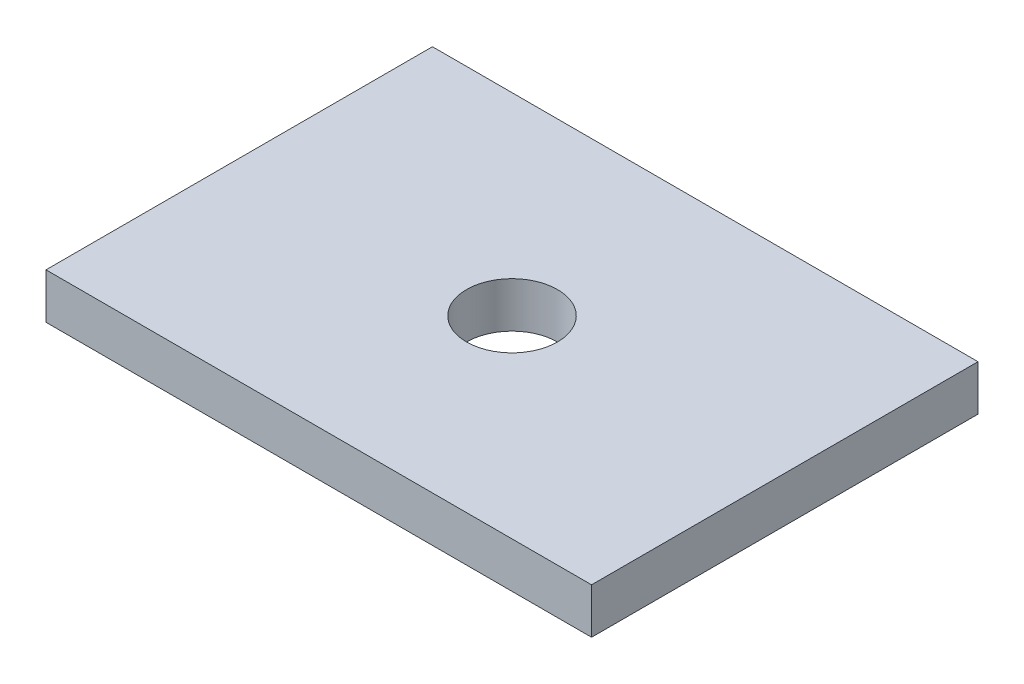
SolidWorks part; units mm, degrees
ref_plane "Front Plane" through (0, 0, 0) normal (0, 0, 1) x (1, 0, 0)
ref_plane "Top Plane" through (0, 0, 0) normal (0, 1, 0) x (1, 0, 0)
ref_plane "Right Plane" through (0, 0, 0) normal (1, 0, 0) x (0, 0, -1)
sketch "Sketch1" plane through (0, 0, 0) normal (0, 1, 0) x (1, 0, 0)
  line L1 (-24, 17) -> (24, 17)
  line L2 (-24, 17) -> (-24, -17)
  line L3 (-24, -17) -> (24, -17)
  line L4 (24, 17) -> (24, -17)
  line L5 (-24, 17) -> (24, -17) construction
  line L6 (-24, -17) -> (24, 17) construction
  circle A0 centre (0, 0) radius 4
  point P0 (0, 0)
  dimension "D3" = 8
  dimension "D1" = 48
  dimension "D2" = 34
extrude "Boss-Extrude1" add sketch "Sketch1" along normal blind 4
